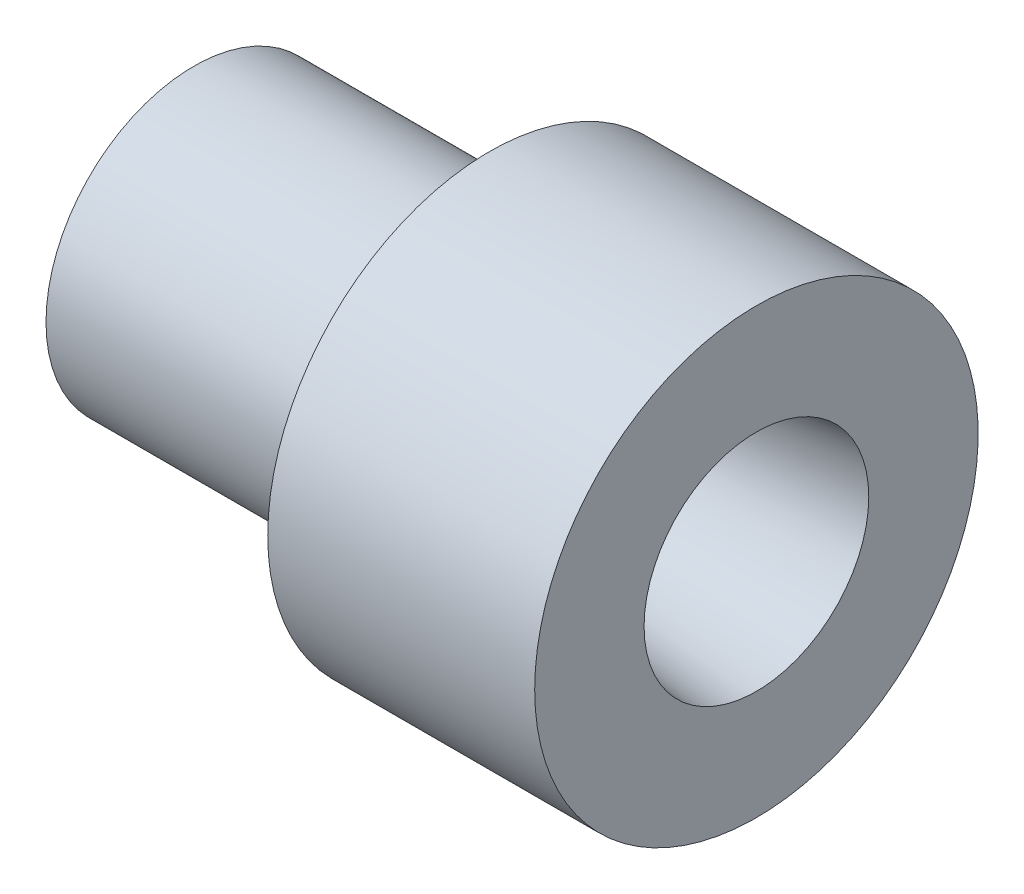
SolidWorks part; units mm, degrees
ref_plane "Front Plane" through (0, 0, 0) normal (0, 0, 1) x (1, 0, 0)
ref_plane "Top Plane" through (0, 0, 0) normal (0, 1, 0) x (1, 0, 0)
ref_plane "Right Plane" through (0, 0, 0) normal (1, 0, 0) x (0, 0, -1)
sketch "Sketch1" plane through (0, 0, 0) normal (0, 1, 0) x (1, 0, 0)
  line L0 (0, 0) -> (0, 2.286) construction
  line L1 (0, 2.286) -> (0, 6.35)
  line L2 (12.7, 9.525) -> (24.1665, 9.525)
  line L3 (24.1665, 9.525) -> (24.1665, 4.826)
  line L4 (24.1665, 4.826) -> (0, 2.286)
  line L5 (0, 0) -> (24.1665, 0) construction
  line L6 (24.1665, 0) -> (24.1665, 4.826) construction
  line L8 (12.7, 6.35) -> (12.7, 9.525)
  line L12 (0, 6.35) -> (12.7, 6.35)
  dimension "D1" = 2.286
  dimension "D2" = 4.826
  dimension "D3" = 6
  dimension "D4" = 9.525
  dimension "D5" = 6.35
  dimension "D6" = 12.7
revolve "Revolve1" add sketch "Sketch1" angle 360 about L5
equation "\"z\" = 8\t\t\t\t'number of blades"
equation "\"de\" = 0.43in\t\t\t'entrance eye diameter"
equation "\"de_length\" = 4mm\t\t'entrance eye consistent length"
equation "\"d_exit\" = 0.18in \t\t'throat aka d1"
equation "\"d2\" = 2.1in \t\t\t'outer diameter of the impeller"
equation "\"b2\" = .2in\t\t\t'tip height from disc surface at d2; slightly higher than d_exit"
equation "\"b1\" = \"b2\" + (\"d2\"/2 - \"de\"/2)*tan(\"theta\") \t\t\t'tip height from disc surface at inlet eye"
equation "\"theta\" = 12\t\t\t'angle of blades from inner to outer "
equation "\"ae\" = 3.14*(\"de\"^2)/4\t\t'entrance eye area'"
equation "\"ce\" = 3.14*\"de\"\t\t'entrance eye circumference"
equation "\"av_ratio\" = .325\t\t'ratio of av/ae at N_s of 470, range is .275 to .375, .325 ideal. High ratio means bigger area means smaller blades"
equation "\"av\" = \"ae\"*\"av_ratio\"\t\t'area between just two blades"
equation "\"s_open\" = \"av\"/\"b1\"\t\t'width of open area"
equation "\"s\"=\"ce\" - \"z\"*\"s_open\""
equation "\"min blade thickness\" = .15in"
equation "\"bearing OD\" = 30mm"
equation "\"bearing ID\"= 10mm"
equation "\"bearing depth\"= 9mm"
equation "\"bearing outer race thickness\"= 1mm"
equation "\"bearing inner race thickness\"= 1mm"
equation "\"bearing bore\" = \"bearing depth\" + 1mm"
equation "\"lower seal OD\" = .917in\t\t'this is https://www.mcmaster.com/#9281k121/=174001b"
equation "\"lower seal ID\"= .375in"
equation "\"lower seal depth\" = .625in + .218in"
equation "\"lower seal bore\" = \"lower seal depth\" + 1mm"
equation "\"upper seal OD\" = 1.125in\t'this is https://www.mcmaster.com/#5154t33/=173zuau, needs to be visually inspected before machining!"
equation "\"upper seal ID\"= 0.625in"
equation "\"upper seal depth\"= .25in\t'aka height; these values need to be confirmed by inspection!! We may want to compress the height."
equation "\"upper seal bore\" = \"upper seal depth\" + 1mm"
equation "\"big o-ring thickness\" = .139in"
equation "\"big o-ring OD\" = 2.734in"
equation "\"big o-ring ID\" = 3.012in"
equation "\"big o-ring groove depth\" = \"big o-ring thickness\"*4/5"
equation "\"impeller center height\" = \"impeller base thickness\" + \"b1\"\t'impeller height at de"
equation "\"impeller outer height\" = \"impeller base thickness\" + \"b2\"\t'impeller height at de"
equation "\"impeller upper clearance\"= .5mm"
equation "\"impeller horizontal clearance\"= (\"d2\"*1.15 - \"d2\")/2 \t\t'clearance based on D2-D3 ratio for circular volute, ranges 1.15 to 1.2"
equation "\"impeller bottom clearance\"= .5mm"
equation "\"impeller base thickness\"= 2mm"
equation "\"impeller dowel diameter\" = 2mm"
equation "\"impeller bolt head diameter\" = \"m4 head bore diameter\""
equation "\"impeller bolt head depth\" = 4mm"
equation "\"impeller bolt stop depth\" = 3mm"
equation "\"impeller bolt bore\" = \"m4 clearance\""
equation "\"impeller shaft bore depth\" = 12mm"
equation "\"impeller shaft bore\" = 8mm"
equation "\"impeller boss depth\" = \"impeller shaft bore depth\"+\"impeller bolt stop depth\"+\"impeller bolt head depth\"-\"impeller base thickness\""
equation "\"impeller boss diameter\" = \"upper seal ID\""
equation "\"impeller dowel length\" = 2mm*2 + \"impeller shaft bore\""
equation "\"coupler motor shaft hole ID\"= 8mm"
equation "\"coupler OD\"= 17mm"
equation "\"coupler length\"= 25mm"
equation "\"motor OD\" = 64mm"
equation "\"motor shaft diameter\"= 8mm"
equation "\"motor shaft pride\"= 32mm"
equation "\"motor to bearing plate distance\" = \"motor shaft pride\" + 2mm +\"coupler length\"/2"
equation "\"square plate bolt bore\" = \"m8 clearance\""
equation "\"square plate bolt head diameter\" = 13.5mm"
equation "\"square plate bolt head depth\" = 8mm"
equation "\"square plate bolt pattern diameter\"= 3.5in"
equation "\"motor mount center bore\"= \"coupler OD\"+ 4mm"
equation "\"motor mount post radius\"= ( 3 * \"square plate bolt bore\" ) / 2"
equation "\"motor mount m4 screw hole diameter\"= 4mm"
equation "\"motor mount m4 head diameter\"= 7.25mm"
equation "\"motor mount m4 head depth\"= 4mm"
equation "\"motor mount m4 pattern diamater\" = 30mm"
equation "\"motor mount plate thickness\"= 8mm + \"motor mount m4 head depth\""
equation "\"bearing plate stop ID\" = \"bearing OD\" - 4mm"
equation "\"bearing plate stop depth\" = 3mm"
equation "\"bearing plate thickness\" = \"bearing bore\" + \"bearing plate stop depth\" + \"shaft bearing stop length\""
equation "\"lower seal plate lip depth\" = 2mm"
equation "\"lower seal plate lip ID\" = \"lower seal OD\" - 3mm"
equation "\"lower seal plate thickness\" = \"lower seal plate lip depth\" + \"lower seal bore\""
equation "\"shaft coupler section diameter\" = 8mm"
equation "\"shaft coupler section length\" = \"motor to bearing plate distance\" - \"motor shaft pride\" - 2mm"
equation "\"shaft bearing section diameter\" = \"bearing ID\""
equation "\"shaft bearing section length\" = \"bearing plate stop depth\" + \"bearing depth\""
equation "\"shaft bearing stop diameter\" = \"bearing ID\" + 4mm"
equation "\"shaft bearing stop length\" = 3mm"
equation "\"shaft lower seal section diameter\" = \"lower seal ID\""
equation "\"shaft lower seal section length\" = \"lower seal plate thickness\" + 1mm"
equation "\"shaft impeller section diameter\" = \"impeller shaft bore\""
equation "\"shaft impeller section length\" = \"upper seal plate thickness\" + \"upper seal plate riser\" + \"impeller bottom clearance\" + \"impeller base thickness\" - \"impeller bolt head depth\" - \"impeller bolt stop depth\""
equation "\"upper seal plate thickness\" = \"upper seal plate pressure hole diameter\"+10mm"
equation "\"upper seal plate lip ID\" = \"upper seal OD\" - 3mm"
equation "\"upper seal plate riser\" = 6.59mm \t\t'this number needs to be read from the housing file"
equation "\"upper seal plate pressure hole diameter\" = .125in\t'this is 1/8 drill "
equation "\"upper seal plate pressure tap diameter\" = .328125in \t'this is 21/64 drill for a 1/8 ANPT tap"
equation "\"upper seal plate pressure tap grip\" = 5mm\t\t'this is the area around the tap so it doesn't crack"
equation "\"upper seal plate pressure tap depth\" = 12mm"
equation "\"impeller cavity center height\"= \"impeller bottom clearance\" + \"impeller upper clearance\" + \"impeller center height\""
equation "\"impeller cavity diameter\"= 2 * \"impeller horizontal clearance\" + \"d2\" \t\t\t\t\t\t\t\t\t'called D3 analytically"
equation "\"impeller cavity outer height\"= \"impeller bottom clearance\" + \"impeller upper clearance\" + \"impeller base thickness\" + \"b2\" \t\t'this is height at impeller diameter d2, not at d3"
equation "\"impeller housing thickness\"= \"impeller housing exit threaded diameter\" + 2*\"impeller housing outlet grip\""
equation "\"impeller housing diameter\" = 4.5in"
equation "\"impeller housing bolt count\" = 8"
equation "\"impeller housing bolt diameter\" = \"m6 clearance\""
equation "\"impeller housing bolt pattern diameter\" = 3.5in"
equation "\"impeller housing threaded inlet diameter\" = 0.71875in \t'this is the 23/32 drill size for 1/2 NPT fitting https://www.mcmaster.com/#50715k269/=176pljy"
equation "\"impeller housing threaded inlet depth\"= .6in"
equation "\"impeller housing exit threaded diameter\"= 0.515625in \t\t'this is the 33/64 drill size for 9/16-18 fitting, expecting swagelok SS-8FK0-1-6STH fitting"
equation "\"impeller housing exit threaded depth\"= 10mm"
equation "\"impeller housing diffuser conical angle\"=10"
equation "\"impeller housing diffuser tangent angle\"=5"
equation "\"impeller housing diffuser final diameter\" = .38in\t\t'aka d2'"
equation "\"impeller housing outlet grip\" = 5mm"
equation "\"end mill size\" = 0.375in\t'for 3/8 endmill"
equation "\"m4 clearance\" = 0.171875in \t'this is 11/64 bit for 4.36mm"
equation "\"m4 tap\" = 0.125in\t\t'this is 1/8 bit for 3.17mm"
equation "\"m4 head bore diameter\" = 7.5mm"
equation "\"m4 head bore depth\" = 5mm\t'actual is ~4mm"
equation "\"m6 clearance\" = 0.234375in\t'this is 15/64 bit = 5.95mm, could use 6mm bit, B bit for 6.04mm or 1/4 bit for 6.35mm"
equation "\"m6 tap\" = 5mm\t\t\t'5mm is appropriate, could use 13/64 or #5,6,7"
equation "\"m6 head bore diameter\" = 11mm\t\t"
equation "\"m6 head bore depth\" = 7mm\t'actual is 6mm"
equation "\"m8 clearance\" = 0.3125in\t'this is 5/16in for 7.93mm, could use 8mm, O,P, or 21/64"
equation "\"m8 tap\" = 0.265625in\t\t'this is 17/64 for 6.746875mm"
equation "\"m8 head bore diameter\" = 14mm"
equation "\"m8 head bore depth\" = 9mm\t'actual is 8mm"
equation "\"D1@Sketch1\"=\"d_exit\"/2"
equation "\"D2@Sketch1\"=\"impeller housing diffuser final diameter\"/2"
equation "\"diffuser cartridge OD\" =.75in"
equation "\"D4@Sketch1\"=\"diffuser cartridge OD\"/2"
